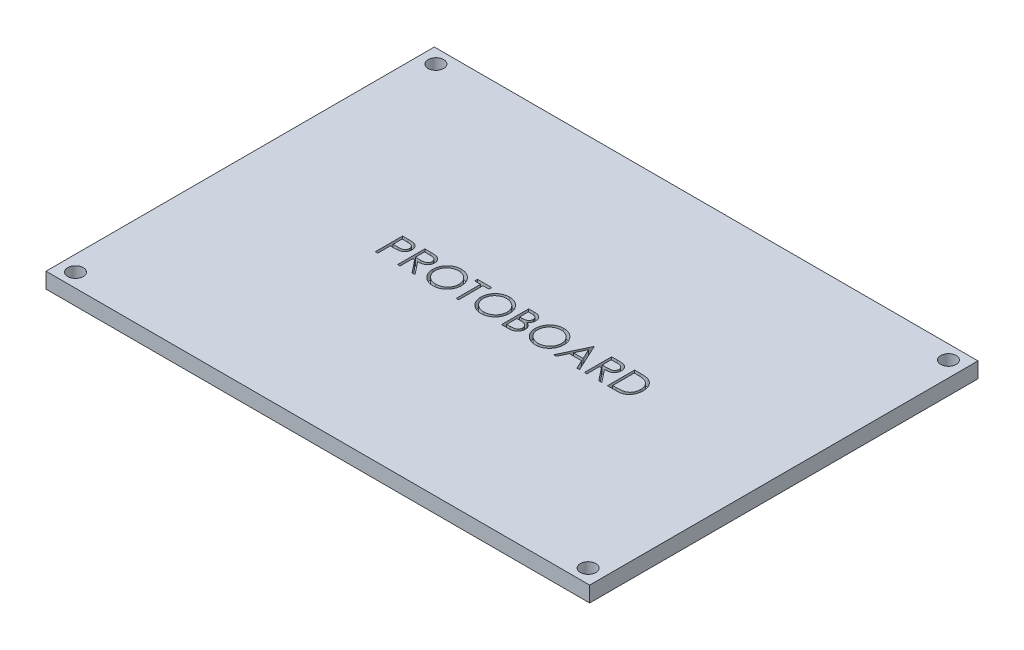
SolidWorks part; units mm, degrees
ref_plane "Front Plane" through (0, 0, 0) normal (0, 0, 1) x (1, 0, 0)
ref_plane "Top Plane" through (0, 0, 0) normal (0, 1, 0) x (1, 0, 0)
ref_plane "Right Plane" through (0, 0, 0) normal (1, 0, 0) x (0, 0, -1)
sketch "Szkic1" plane through (0, 0, 0) normal (0, 1, 0) x (1, 0, 0)
  line L0 (-35, -25) -> (35, 25) construction
  line L1 (-35, 25) -> (35, 25)
  line L2 (-35, 25) -> (-35, -25)
  line L3 (-35, -25) -> (35, -25)
  line L4 (35, 25) -> (35, -25)
  dimension "D1" = 70
  dimension "D2" = 50
extrude "Dodanie-wyciągnięcie1" add sketch "Szkic1" along normal blind 2
sketch "Szkic2" plane through (0, 2, 0) normal (0, 1, 0) x (1, 0, 0)
  line L0 (-33, 23.2) -> (-35, 25) construction
  line L1 (35, -25) -> (33, -23.2) construction
  line L2 (33, 23.2) -> (35, 25) construction
  circle A0 centre (-33, 23.2) radius 1
  circle A1 centre (33, 23.2) radius 1
  circle A2 centre (-33, -23.2) radius 1
  circle A3 centre (33, -23.2) radius 1
  dimension "D2" = 2
  dimension "D1" = 66
  dimension "D3" = 46.4
extrude "Wytnij-wyciągnięcie1" cut sketch "Szkic2" against normal blind 2
sketch "Szkic3" plane through (0, 2, 0) normal (0, 1, 0) x (1, 0, 0)
  text T0 "PROTOBOARD"
extrude "Wytnij-wyciągnięcie2" cut sketch "Szkic3" against normal blind 1
